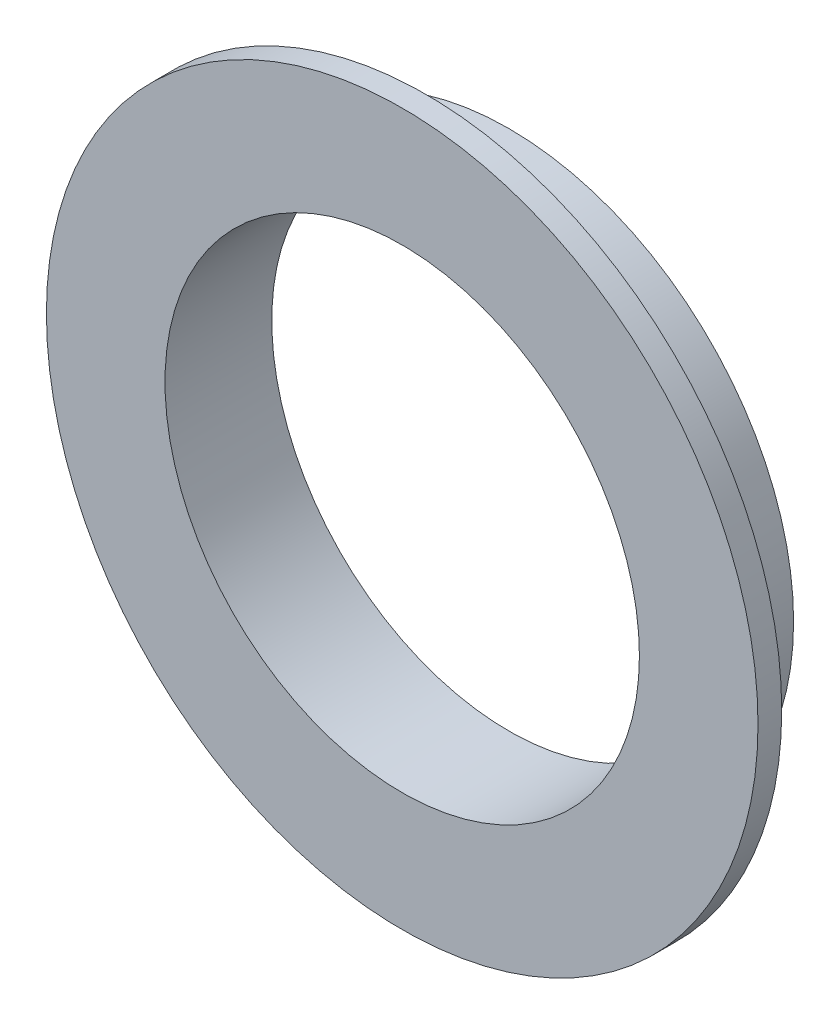
SolidWorks part; units mm, degrees
material "Nylon 101"
ref_plane "Front" through (0, 0, 0) normal (0, 0, 1) x (1, 0, 0)
ref_plane "Top" through (0, 0, 0) normal (0, 1, 0) x (1, 0, 0)
ref_plane "Right" through (0, 0, 0) normal (1, 0, 0) x (0, 0, -1)
sketch "Sketch1" plane through (0, 0, 0) normal (0, 0, 1) x (1, 0, 0)
  circle A0 centre (0, 0) radius 10
  circle A1 centre (0, 0) radius 12
  dimension "D1" = 2
  dimension "D2" = 20
extrude "Boss-Extrude1" add sketch "Sketch1" along normal blind 4.5
sketch "Sketch2" plane through (0, 0, 4.5) normal (0, 0, 1) x (1, 0, 0)
  circle A0 centre (0, 0) radius 11
  circle A1 centre (0, 0) radius 15
  dimension "D1" = 4
  dimension "D2" = 22
extrude "Boss-Extrude2" add sketch "Sketch2" against normal blind 1
scale "Scale1" scale about centroid uniform scaling yes scale factor 1.013
